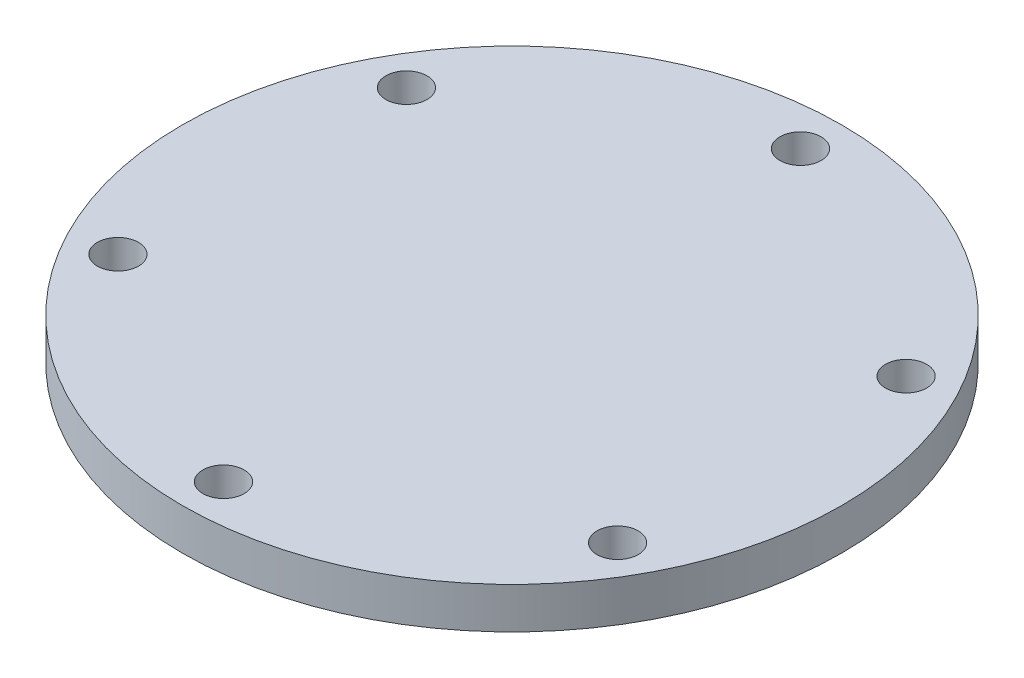
SolidWorks part; units mm, degrees
ref_plane "Front Plane" through (0, 0, 0) normal (0, 0, 1) x (1, 0, 0)
ref_plane "Top Plane" through (0, 0, 0) normal (0, 1, 0) x (1, 0, 0)
ref_plane "Right Plane" through (0, 0, 0) normal (1, 0, 0) x (0, 0, -1)
ref_axis "Centerline" through (0, 21.4963, 0) along (0, -1, 0)
sketch "Sketch1" plane through (0, 0, 0) normal (0, 1, 0) x (1, 0, 0)
  circle A0 centre (0, 0) radius 20.32
  dimension "D1" = 40.64
extrude "Cylinder" add sketch "Sketch1" along normal blind 14.478
sketch "Sketch2" plane through (0, 0, 0) normal (0, 0, 1) x (1, 0, 0)
  line L0 (0, 20.1077) -> (0, -7.6632) construction
  line L1 (20.32, 0) -> (12.7, 0)
  line L2 (20.32, 0) -> (20.32, 11.938)
  line L3 (20.32, 11.938) -> (12.7, 11.938)
  line L4 (12.7, 0) -> (12.7, 11.938)
  line L5 (20.32, 14.478) -> (-20.32, 14.478) construction
  dimension "D1" = 12.7
  dimension "D2" = 2.54
revolve "Mid O Ring Wings" cut sketch "Sketch2" angle 360 about axis through (0, 21.4963, 0) along (0, -1, 0)
sketch "Sketch3" plane through (0, 0, 0) normal (0, 0, 1) x (1, 0, 0)
  line L0 (12.7, 0) -> (12.7, 11.938) construction
  line L1 (12.7, 10.668) -> (10.414, 10.668)
  line L2 (12.7, 10.668) -> (12.7, 7.874)
  line L3 (12.7, 7.874) -> (10.414, 7.874)
  line L4 (10.414, 10.668) -> (10.414, 7.874)
  line L5 (-12.7, 11.938) -> (12.7, 11.938) construction
  dimension "D1" = 1.27
  dimension "D2" = 2.286
  dimension "D3" = 2.794
revolve "Mid O Ring Cut" cut sketch "Sketch3" angle 360 about axis through (0, 21.4963, 0) along (0, -1, 0)
sketch "Sketch4" plane through (0, 0, 0) normal (0, 0, 1) x (1, 0, 0)
  line L0 (12.7, 7.874) -> (-12.7, 7.874) construction
  line L2 (12.7, 0) -> (12.7, 6.604)
  line L3 (12.7, 6.604) -> (3.8252, 6.604)
  line L5 (0, 20.9905) -> (0, -6.9276) construction
  line L6 (3.8252, 0) -> (0, 0) construction
  line L7 (3.8252, 6.604) -> (3.8252, 0)
  line L8 (3.8252, 0) -> (12.7, 0)
  point P10 (0, 0)
  point P12 (5.314, 0)
  point P13 (4.1743, 0)
  point P14 (3.7636, 0)
  dimension "D1" = 1.27
  dimension "D2" = 3.8252
revolve "Bottom O Ring Wings" cut sketch "Sketch4" angle 360 about axis through (0, 21.4963, 0) along (0, -1, 0)
sketch "Sketch5" plane through (0, 0, 0) normal (0, 0, 1) x (1, 0, 0)
  line L0 (3.8252, 0) -> (3.8252, 6.604) construction
  line L1 (3.8252, 5.334) -> (1.5392, 5.334)
  line L2 (3.8252, 5.334) -> (3.8252, 2.54)
  line L3 (3.8252, 2.54) -> (1.5392, 2.54)
  line L4 (1.5392, 5.334) -> (1.5392, 2.54)
  line L5 (-3.8252, 6.604) -> (3.8252, 6.604) construction
  dimension "D1" = 1.27
  dimension "D2" = 2.794
  dimension "D3" = 2.286
revolve "Bottom O Ring Cut" cut sketch "Sketch5" angle 360 about axis through (0, 21.4963, 0) along (0, -1, 0)
chamfer "Bottom Chamfer" distance 3.81 distance2 1.27 1 edges at (0, 0, 3.8252)
sketch "Sketch6" plane through (0, 14.478, 0) normal (0, 1, 0) x (1, 0, 0)
  circle A0 centre (0, 17.78) radius 1.27
  circle A1 centre (0, 0) radius 20.32 construction
  dimension "D1" = 2.54
  dimension "D2" = 17.78
extrude "Mounting Hole" cut sketch "Sketch6" against normal up to next
pattern_circular "Mounting Hole Pattern" count 6 over 360 about axis through (0, 0, 0) along (0, 1, 0) of "Mounting Hole"
